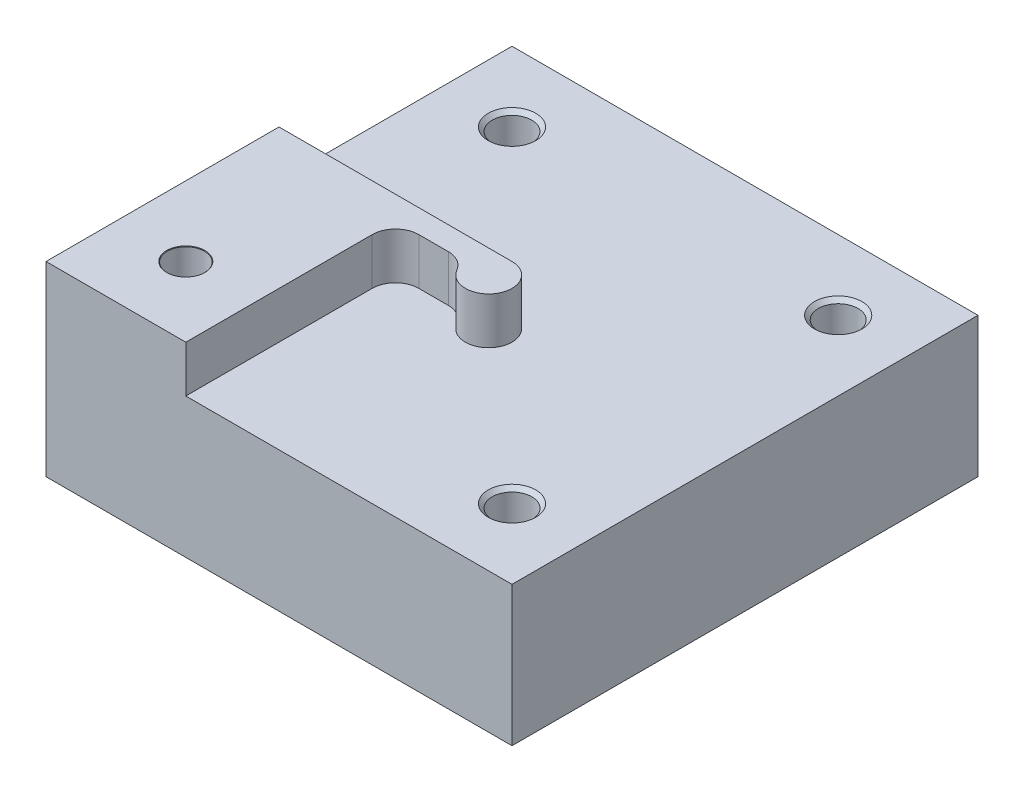
SolidWorks part; units mm, degrees
ref_plane "Front Plane" through (0, 0, 0) normal (0, 0, 1) x (1, 0, 0)
ref_plane "Top Plane" through (0, 0, 0) normal (0, 1, 0) x (1, 0, 0)
ref_plane "Right Plane" through (0, 0, 0) normal (1, 0, 0) x (0, 0, -1)
sketch "Sketch2" plane through (0, 0, 0) normal (0, 1, 0) x (1, 0, 0)
  line L1 (-50, 50) -> (50, 50)
  line L2 (-50, 50) -> (-50, -50)
  line L3 (-50, -50) -> (50, -50)
  line L4 (50, 50) -> (50, -50)
  dimension "D1" = 100
  dimension "D2" = 100
  dimension "D3" = 50
  dimension "D4" = 50
extrude "Boss-Extrude1" add sketch "Sketch2" along normal blind 30
sketch "Sketch4" plane through (0, 30, 0) normal (0, 1, 0) x (1, 0, 0)
  line L0 (-50, -50) -> (-50, 0)
  line L1 (-50, 50) -> (-50, -50) construction
  line L2 (-50, 0) -> (0, 0)
  line L3 (-8.6603, -5) -> (-15, -5)
  line L4 (-20, -10) -> (-20, -50)
  line L5 (-50, -50) -> (50, -50) construction
  line L6 (-20, -50) -> (-50, -50)
  arc A0 (0, 0) -> (-4.3301, -7.5) centre (0, -5) cw
  arc A1 (-15, -5) -> (-20, -10) centre (-15, -10) ccw
  arc A2 (-4.3301, -7.5) -> (-8.6603, -5) centre (-8.6603, -10) ccw
  point P14 (-20, -5)
  point P17 (-5, -5)
  dimension "D5" = 5
  dimension "D1" = 50
  dimension "D2" = 30
  dimension "D3" = 50
  dimension "D4" = 15
extrude "Boss-Extrude2" add sketch "Sketch4" along normal blind 10
sketch "Sketch5" plane through (0, 30, 0) normal (0, 1, 0) x (1, 0, 0)
  line L0 (50, -50) -> (50, 50) construction
  line L1 (50, 50) -> (-50, 50) construction
  line L2 (-50, 50) -> (-50, 0) construction
  line L3 (-20, -50) -> (50, -50) construction
  circle A0 centre (35, 35) radius 4.25
  circle A1 centre (-35, 35) radius 4.25
  circle A2 centre (35, -35) radius 4.25
  dimension "D1" = 8.5
  dimension "D2" = 8.5
  dimension "D3" = 8.5
  dimension "D4" = 15
  dimension "D5" = 15
  dimension "D6" = 15
  dimension "D7" = 15
  dimension "D8" = 15
  dimension "D9" = 15
extrude "Cut-Extrude1" cut sketch "Sketch5" against normal blind 15
chamfer "Chamfer1" distance 0.85 angle 45 3 edges at (35, 30, 39.25) (35, 30, -30.75) (-35, 30, -30.75)
sketch "Sketch7" plane through (0, 40, 0) normal (0, 1, 0) x (1, 0, 0)
  line L0 (-50, -50) -> (-20, -50) construction
  line L1 (-50, 0) -> (-50, -50) construction
  circle A0 centre (-35, -35) radius 4
  dimension "D1" = 8
  dimension "D2" = 15
  dimension "D3" = 15
extrude "Cut-Extrude2" cut sketch "Sketch7" against normal blind 15
chamfer "Chamfer2" distance 0.1 angle 45 1 edges at (-35, 40, 39)
